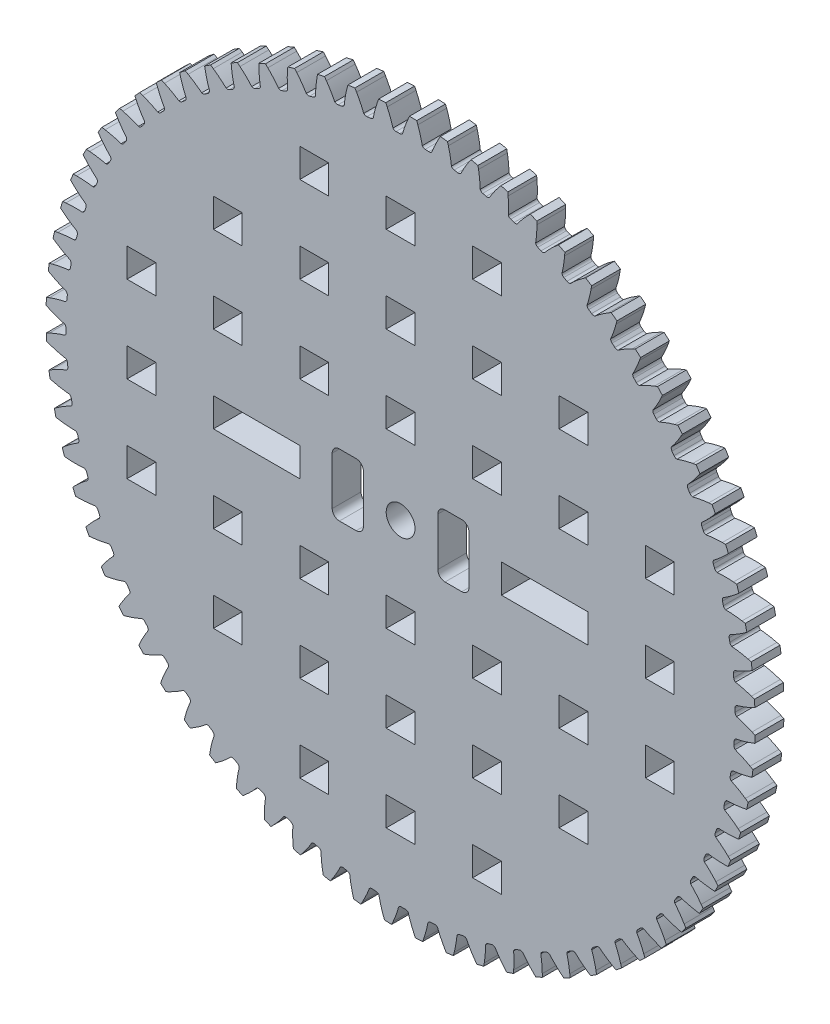
SolidWorks part; units mm, degrees
ref_plane "Alzado" through (0, 0, 0) normal (0, 0, 1) x (1, 0, 0)
ref_plane "Planta" through (0, 0, 0) normal (0, 1, 0) x (1, 0, 0)
ref_plane "Vista lateral" through (0, 0, 0) normal (1, 0, 0) x (0, 0, -1)
sketch "Model" plane through (0, 0, 0) normal (0, 0, 1) x (1, 0, 0)
  line L0 (42.6187, 265.9479) -> (42.6187, 262.9479)
  line L1 (45.6187, 265.9479) -> (42.6187, 265.9479)
  line L2 (45.6187, 262.9479) -> (45.6187, 265.9479)
  line L3 (42.6187, 262.9479) -> (45.6187, 262.9479)
  line L4 (72.6187, 238.9479) -> (69.6187, 238.9479)
  line L5 (72.6187, 235.9479) -> (72.6187, 238.9479)
  line L6 (69.6187, 235.9479) -> (72.6187, 235.9479)
  line L7 (69.6187, 238.9479) -> (69.6187, 235.9479)
  line L8 (72.6187, 256.9479) -> (69.6187, 256.9479)
  line L9 (72.6187, 253.9479) -> (72.6187, 256.9479)
  line L10 (69.6187, 253.9479) -> (72.6187, 253.9479)
  line L11 (69.6187, 256.9479) -> (69.6187, 253.9479)
  line L12 (42.6187, 256.9479) -> (42.6187, 253.9479)
  line L13 (45.6187, 256.9479) -> (42.6187, 256.9479)
  line L14 (45.6187, 253.9479) -> (45.6187, 256.9479)
  line L15 (42.6187, 253.9479) -> (45.6187, 253.9479)
  line L16 (51.6187, 256.9479) -> (51.6187, 253.9479)
  line L17 (54.6187, 256.9479) -> (51.6187, 256.9479)
  line L18 (54.6187, 253.9479) -> (54.6187, 256.9479)
  line L19 (51.6187, 253.9479) -> (54.6187, 253.9479)
  line L20 (60.6187, 256.9479) -> (60.6187, 253.9479)
  line L21 (63.6187, 256.9479) -> (60.6187, 256.9479)
  line L22 (63.6187, 253.9479) -> (63.6187, 256.9479)
  line L23 (60.6187, 253.9479) -> (63.6187, 253.9479)
  line L24 (42.6187, 238.9479) -> (42.6187, 235.9479)
  line L25 (45.6187, 238.9479) -> (42.6187, 238.9479)
  line L26 (45.6187, 235.9479) -> (45.6187, 238.9479)
  line L27 (42.6187, 235.9479) -> (45.6187, 235.9479)
  line L28 (51.6187, 238.9479) -> (51.6187, 235.9479)
  line L29 (54.6187, 238.9479) -> (51.6187, 238.9479)
  line L30 (54.6187, 235.9479) -> (54.6187, 238.9479)
  line L31 (51.6187, 235.9479) -> (54.6187, 235.9479)
  line L32 (60.6187, 238.9479) -> (60.6187, 235.9479)
  line L33 (63.6187, 238.9479) -> (60.6187, 238.9479)
  line L34 (63.6187, 235.9479) -> (63.6187, 238.9479)
  line L35 (60.6187, 235.9479) -> (63.6187, 235.9479)
  line L36 (42.6187, 229.9479) -> (42.6187, 226.9479)
  line L37 (45.6187, 229.9479) -> (42.6187, 229.9479)
  line L38 (45.6187, 226.9479) -> (45.6187, 229.9479)
  line L39 (42.6187, 226.9479) -> (45.6187, 226.9479)
  line L40 (51.6187, 229.9479) -> (51.6187, 226.9479)
  line L41 (54.6187, 229.9479) -> (51.6187, 229.9479)
  line L42 (54.6187, 226.9479) -> (54.6187, 229.9479)
  line L43 (51.6187, 226.9479) -> (54.6187, 226.9479)
  line L44 (60.6187, 229.9479) -> (60.6187, 226.9479)
  line L45 (63.6187, 229.9479) -> (60.6187, 229.9479)
  line L46 (63.6187, 226.9479) -> (63.6187, 229.9479)
  line L47 (60.6187, 226.9479) -> (63.6187, 226.9479)
  line L48 (36.6187, 238.9479) -> (33.6187, 238.9479)
  line L49 (36.6187, 235.9479) -> (36.6187, 238.9479)
  line L50 (33.6187, 235.9479) -> (36.6187, 235.9479)
  line L51 (33.6187, 238.9479) -> (33.6187, 235.9479)
  line L52 (36.6187, 256.9479) -> (33.6187, 256.9479)
  line L53 (36.6187, 253.9479) -> (36.6187, 256.9479)
  line L54 (33.6187, 253.9479) -> (36.6187, 253.9479)
  line L55 (33.6187, 256.9479) -> (33.6187, 253.9479)
  line L56 (33.6187, 247.9479) -> (33.6187, 244.9479)
  line L57 (42.6187, 247.9479) -> (33.6187, 247.9479)
  line L58 (42.6187, 244.9479) -> (42.6187, 247.9479)
  line L59 (33.6187, 244.9479) -> (42.6187, 244.9479)
  line L60 (60.6187, 274.9479) -> (60.6187, 271.9479)
  line L61 (63.6187, 274.9479) -> (60.6187, 274.9479)
  line L62 (63.6187, 271.9479) -> (63.6187, 274.9479)
  line L63 (60.6187, 271.9479) -> (63.6187, 271.9479)
  line L64 (51.6187, 274.9479) -> (51.6187, 271.9479)
  line L65 (54.6187, 274.9479) -> (51.6187, 274.9479)
  line L66 (54.6187, 271.9479) -> (54.6187, 274.9479)
  line L67 (51.6187, 271.9479) -> (54.6187, 271.9479)
  line L68 (42.6187, 274.9479) -> (42.6187, 271.9479)
  line L69 (45.6187, 274.9479) -> (42.6187, 274.9479)
  line L70 (45.6187, 271.9479) -> (45.6187, 274.9479)
  line L71 (42.6187, 271.9479) -> (45.6187, 271.9479)
  line L72 (24.6187, 253.9479) -> (27.6187, 253.9479)
  line L73 (24.6187, 256.9479) -> (24.6187, 253.9479)
  line L74 (27.6187, 256.9479) -> (24.6187, 256.9479)
  line L75 (27.6187, 253.9479) -> (27.6187, 256.9479)
  line L76 (24.6187, 244.9479) -> (27.6187, 244.9479)
  line L77 (24.6187, 247.9479) -> (24.6187, 244.9479)
  line L78 (27.6187, 247.9479) -> (24.6187, 247.9479)
  line L79 (27.6187, 244.9479) -> (27.6187, 247.9479)
  line L80 (24.6187, 235.9479) -> (27.6187, 235.9479)
  line L81 (24.6187, 238.9479) -> (24.6187, 235.9479)
  line L82 (27.6187, 238.9479) -> (24.6187, 238.9479)
  line L83 (27.6187, 235.9479) -> (27.6187, 238.9479)
  line L84 (45.6187, 217.9479) -> (45.6187, 220.9479)
  line L85 (42.6187, 217.9479) -> (45.6187, 217.9479)
  line L86 (42.6187, 220.9479) -> (42.6187, 217.9479)
  line L87 (45.6187, 220.9479) -> (42.6187, 220.9479)
  line L88 (54.6187, 217.9479) -> (54.6187, 220.9479)
  line L89 (51.6187, 217.9479) -> (54.6187, 217.9479)
  line L90 (51.6187, 220.9479) -> (51.6187, 217.9479)
  line L91 (54.6187, 220.9479) -> (51.6187, 220.9479)
  line L92 (63.6187, 217.9479) -> (63.6187, 220.9479)
  line L93 (60.6187, 217.9479) -> (63.6187, 217.9479)
  line L94 (60.6187, 220.9479) -> (60.6187, 217.9479)
  line L95 (63.6187, 220.9479) -> (60.6187, 220.9479)
  line L96 (81.6187, 238.9479) -> (78.6187, 238.9479)
  line L97 (81.6187, 235.9479) -> (81.6187, 238.9479)
  line L98 (78.6187, 235.9479) -> (81.6187, 235.9479)
  line L99 (78.6187, 238.9479) -> (78.6187, 235.9479)
  line L100 (81.6187, 247.9479) -> (78.6187, 247.9479)
  line L101 (81.6187, 244.9479) -> (81.6187, 247.9479)
  line L102 (78.6187, 244.9479) -> (81.6187, 244.9479)
  line L103 (78.6187, 247.9479) -> (78.6187, 244.9479)
  line L104 (81.6187, 256.9479) -> (78.6187, 256.9479)
  line L105 (81.6187, 253.9479) -> (81.6187, 256.9479)
  line L106 (78.6187, 253.9479) -> (81.6187, 253.9479)
  line L107 (78.6187, 256.9479) -> (78.6187, 253.9479)
  line L108 (33.6187, 265.9479) -> (33.6187, 262.9479)
  line L109 (36.6187, 265.9479) -> (33.6187, 265.9479)
  line L110 (36.6187, 262.9479) -> (36.6187, 265.9479)
  line L111 (33.6187, 262.9479) -> (36.6187, 262.9479)
  line L112 (33.6187, 229.9479) -> (33.6187, 226.9479)
  line L113 (36.6187, 229.9479) -> (33.6187, 229.9479)
  line L114 (36.6187, 226.9479) -> (36.6187, 229.9479)
  line L115 (33.6187, 226.9479) -> (36.6187, 226.9479)
  line L116 (69.6187, 265.9479) -> (69.6187, 262.9479)
  line L117 (72.6187, 265.9479) -> (69.6187, 265.9479)
  line L118 (72.6187, 262.9479) -> (72.6187, 265.9479)
  line L119 (69.6187, 262.9479) -> (72.6187, 262.9479)
  line L120 (69.6187, 229.9479) -> (69.6187, 226.9479)
  line L121 (72.6187, 229.9479) -> (69.6187, 229.9479)
  line L122 (72.6187, 226.9479) -> (72.6187, 229.9479)
  line L123 (69.6187, 226.9479) -> (72.6187, 226.9479)
  line L124 (51.6187, 265.9479) -> (51.6187, 262.9479)
  line L125 (54.6187, 265.9479) -> (51.6187, 265.9479)
  line L126 (54.6187, 262.9479) -> (54.6187, 265.9479)
  line L127 (51.6187, 262.9479) -> (54.6187, 262.9479)
  line L128 (63.6187, 247.9479) -> (63.6187, 244.9479)
  line L129 (72.6187, 247.9479) -> (63.6187, 247.9479)
  line L130 (72.6187, 244.9479) -> (72.6187, 247.9479)
  line L131 (63.6187, 244.9479) -> (72.6187, 244.9479)
  line L132 (60.6187, 265.9479) -> (60.6187, 262.9479)
  line L133 (63.6187, 265.9479) -> (60.6187, 265.9479)
  line L134 (63.6187, 262.9479) -> (63.6187, 265.9479)
  line L135 (60.6187, 262.9479) -> (63.6187, 262.9479)
  line L136 (59.4937, 249.6979) -> (57.7437, 249.6979)
  line L137 (60.2437, 243.9479) -> (60.2437, 248.9479)
  line L138 (57.7437, 243.1979) -> (59.4937, 243.1979)
  line L139 (56.9937, 248.9479) -> (56.9937, 243.9479)
  line L140 (46.7437, 249.6979) -> (48.4937, 249.6979)
  line L141 (45.9937, 243.9479) -> (45.9937, 248.9479)
  line L142 (48.4937, 243.1979) -> (46.7437, 243.1979)
  line L143 (49.2437, 248.9479) -> (49.2437, 243.9479)
  line L144 (66.3811, 280.5801) -> (66.6218, 280.8256)
  line L145 (66.6218, 280.8256) -> (67.3121, 280.5464)
  line L146 (67.3121, 280.5464) -> (67.3144, 280.2026)
  line L147 (67.4112, 278.2246) -> (67.7482, 278.0709)
  line L148 (69.3055, 279.2944) -> (69.5666, 279.5179)
  line L149 (69.5666, 279.5179) -> (70.23, 279.1796)
  line L150 (70.23, 279.1796) -> (70.2023, 278.837)
  line L151 (70.1264, 276.8581) -> (70.4487, 276.6755)
  line L152 (72.1066, 277.7586) -> (72.3862, 277.9586)
  line L153 (72.3862, 277.9586) -> (73.0176, 277.5637)
  line L154 (73.0176, 277.5637) -> (72.9602, 277.2248)
  line L155 (72.712, 275.26) -> (73.0172, 275.0501)
  line L156 (74.7633, 275.9846) -> (75.0593, 276.1594)
  line L157 (75.0593, 276.1594) -> (75.6538, 275.711)
  line L158 (75.6538, 275.711) -> (75.5671, 275.3784)
  line L159 (75.1486, 273.4427) -> (75.4344, 273.207)
  line L160 (77.2552, 273.9857) -> (77.5653, 274.1341)
  line L161 (77.5653, 274.1341) -> (78.1185, 273.6356)
  line L162 (78.1185, 273.6356) -> (78.0031, 273.3118)
  line L163 (77.4176, 271.42) -> (77.6817, 271.1602)
  line L164 (79.5634, 271.7773) -> (79.8853, 271.8981)
  line L165 (79.8853, 271.8981) -> (80.3929, 271.3533)
  line L166 (80.3929, 271.3533) -> (80.2498, 271.0407)
  line L167 (79.5015, 269.2072) -> (79.742, 268.9254)
  line L168 (81.6704, 269.3761) -> (82.0015, 269.4684)
  line L169 (82.0015, 269.4684) -> (82.4598, 268.8814)
  line L170 (82.4598, 268.8814) -> (82.2899, 268.5825)
  line L171 (81.3847, 266.8211) -> (81.5997, 266.5195)
  line L172 (83.5601, 266.8004) -> (83.898, 266.8635)
  line L173 (83.898, 266.8635) -> (84.3033, 266.2388)
  line L174 (84.3033, 266.2388) -> (84.1081, 265.9559)
  line L175 (83.0528, 264.2801) -> (83.2407, 263.9608)
  line L176 (85.2181, 264.0698) -> (85.5602, 264.1032)
  line L177 (85.5602, 264.1032) -> (85.9096, 263.4455)
  line L178 (85.9096, 263.4455) -> (85.6904, 263.1807)
  line L179 (84.4931, 261.6033) -> (84.6524, 261.2689)
  line L180 (86.6318, 261.2051) -> (86.9755, 261.2086)
  line L181 (86.9755, 261.2086) -> (87.2662, 260.523)
  line L182 (87.2662, 260.523) -> (87.0248, 260.2782)
  line L183 (85.6946, 258.8112) -> (85.8242, 258.4641)
  line L184 (87.7904, 258.2281) -> (88.1332, 258.2016)
  line L185 (88.1332, 258.2016) -> (88.363, 257.4932)
  line L186 (88.363, 257.4932) -> (88.1012, 257.2705)
  line L187 (86.6481, 255.9249) -> (86.747, 255.568)
  line L188 (88.6852, 255.1615) -> (89.0243, 255.1051)
  line L189 (89.0243, 255.1051) -> (89.1916, 254.3795)
  line L190 (89.1916, 254.3795) -> (88.9113, 254.1804)
  line L191 (87.3465, 252.9666) -> (87.4139, 252.6024)
  line L192 (89.3093, 252.0285) -> (89.6422, 251.9428)
  line L193 (89.6422, 251.9428) -> (89.7456, 251.2053)
  line L194 (89.7456, 251.2053) -> (89.449, 251.0315)
  line L195 (87.7844, 249.9586) -> (87.8198, 249.5899)
  line L196 (89.658, 248.853) -> (89.9821, 248.7387)
  line L197 (89.9821, 248.7387) -> (90.0208, 247.995)
  line L198 (90.0208, 247.995) -> (89.7103, 247.8476)
  line L199 (87.9585, 246.924) -> (87.9616, 246.5536)
  line L200 (89.7285, 245.6593) -> (90.0415, 245.5171)
  line L201 (90.0415, 245.5171) -> (90.0152, 244.7729)
  line L202 (90.0152, 244.7729) -> (89.693, 244.6531)
  line L203 (87.8674, 243.8857) -> (87.8382, 243.5164)
  line L204 (89.5205, 242.4715) -> (89.8199, 242.3026)
  line L205 (89.8199, 242.3026) -> (89.7288, 241.5635)
  line L206 (89.7288, 241.5635) -> (89.3974, 241.4723)
  line L207 (87.5119, 240.8669) -> (87.4506, 240.5016)
  line L208 (89.0354, 239.314) -> (89.3189, 239.1197)
  line L209 (89.3189, 239.1197) -> (89.1638, 238.3913)
  line L210 (89.1638, 238.3913) -> (88.8257, 238.3293)
  line L211 (86.8946, 237.8906) -> (86.8017, 237.532)
  line L212 (88.277, 236.2108) -> (88.5425, 235.9925)
  line L213 (88.5425, 235.9925) -> (88.3245, 235.2804)
  line L214 (88.3245, 235.2804) -> (87.9823, 235.2482)
  line L215 (86.0202, 234.9794) -> (85.8964, 234.6302)
  line L216 (87.251, 233.1856) -> (87.4964, 232.9449)
  line L217 (87.4964, 232.9449) -> (87.2172, 232.2546)
  line L218 (87.2172, 232.2546) -> (86.8735, 232.2522)
  line L219 (84.8955, 232.1555) -> (84.7417, 231.8184)
  line L220 (85.9652, 230.2612) -> (86.1888, 230.0001)
  line L221 (86.1888, 230.0001) -> (85.8504, 229.3367)
  line L222 (85.8504, 229.3367) -> (85.5078, 229.3643)
  line L223 (83.5289, 229.4403) -> (83.3463, 229.118)
  line L224 (84.4294, 227.46) -> (84.6294, 227.1804)
  line L225 (84.6294, 227.1804) -> (84.2345, 226.549)
  line L226 (84.2345, 226.549) -> (83.8956, 226.6064)
  line L227 (81.9308, 226.8546) -> (81.7209, 226.5494)
  line L228 (82.6554, 224.8034) -> (82.8302, 224.5074)
  line L229 (82.8302, 224.5074) -> (82.3818, 223.9128)
  line L230 (82.3818, 223.9128) -> (82.0492, 223.9996)
  line L231 (80.1135, 224.418) -> (79.8778, 224.1323)
  line L232 (80.6565, 222.3115) -> (80.8049, 222.0014)
  line L233 (80.8049, 222.0014) -> (80.3064, 221.4482)
  line L234 (80.3064, 221.4482) -> (79.9826, 221.5635)
  line L235 (78.0908, 222.1491) -> (77.831, 221.885)
  line L236 (78.4481, 220.0032) -> (78.5689, 219.6814)
  line L237 (78.5689, 219.6814) -> (78.0241, 219.1737)
  line L238 (78.0241, 219.1737) -> (77.7115, 219.3169)
  line L239 (75.878, 220.0651) -> (75.5962, 219.8247)
  line L240 (76.0469, 217.8963) -> (76.1392, 217.5651)
  line L241 (76.1392, 217.5651) -> (75.5522, 217.1069)
  line L242 (75.5522, 217.1069) -> (75.2533, 217.2767)
  line L243 (73.492, 218.1819) -> (73.1903, 217.9669)
  line L244 (73.4712, 216.0066) -> (73.5343, 215.6687)
  line L245 (73.5343, 215.6687) -> (72.9096, 215.2633)
  line L246 (72.9096, 215.2633) -> (72.6267, 215.4586)
  line L247 (70.9509, 216.5138) -> (70.6316, 216.326)
  line L248 (70.7407, 214.3486) -> (70.774, 214.0065)
  line L249 (70.774, 214.0065) -> (70.1164, 213.6571)
  line L250 (70.1164, 213.6571) -> (69.8515, 213.8763)
  line L251 (68.2741, 215.0736) -> (67.9397, 214.9142)
  line L252 (67.876, 212.9349) -> (67.8794, 212.5912)
  line L253 (67.8794, 212.5912) -> (67.1938, 212.3004)
  line L254 (67.1938, 212.3004) -> (66.9491, 212.5419)
  line L255 (65.482, 213.8721) -> (65.135, 213.7425)
  line L256 (64.899, 211.7762) -> (64.8724, 211.4335)
  line L257 (64.8724, 211.4335) -> (64.1641, 211.2037)
  line L258 (64.1641, 211.2037) -> (63.9413, 211.4655)
  line L259 (62.5958, 212.9185) -> (62.2388, 212.8197)
  line L260 (61.8323, 210.8815) -> (61.776, 210.5424)
  line L261 (61.776, 210.5424) -> (61.0503, 210.3751)
  line L262 (61.0503, 210.3751) -> (60.8512, 210.6554)
  line L263 (59.6374, 212.2201) -> (59.2732, 212.1528)
  line L264 (58.6993, 210.2574) -> (58.6136, 209.9245)
  line L265 (58.6136, 209.9245) -> (57.8762, 209.8211)
  line L266 (57.8762, 209.8211) -> (57.7023, 210.1176)
  line L267 (56.6295, 211.7822) -> (56.2607, 211.7469)
  line L268 (55.5239, 209.9087) -> (55.4095, 209.5845)
  line L269 (55.4095, 209.5845) -> (54.6658, 209.5458)
  line L270 (54.6658, 209.5458) -> (54.5184, 209.8564)
  line L271 (53.5948, 211.6082) -> (53.2244, 211.6051)
  line L272 (52.3301, 209.8381) -> (52.1879, 209.5252)
  line L273 (52.1879, 209.5252) -> (51.4437, 209.5514)
  line L274 (51.4437, 209.5514) -> (51.3239, 209.8736)
  line L275 (50.5565, 211.6993) -> (50.1872, 211.7285)
  line L276 (49.1424, 210.0462) -> (48.9734, 209.7468)
  line L277 (48.9734, 209.7468) -> (48.2343, 209.8378)
  line L278 (48.2343, 209.8378) -> (48.1431, 210.1693)
  line L279 (47.5377, 212.0548) -> (47.1724, 212.1161)
  line L280 (45.9849, 210.5313) -> (45.7905, 210.2477)
  line L281 (45.7905, 210.2477) -> (45.0621, 210.4028)
  line L282 (45.0621, 210.4028) -> (45.0002, 210.741)
  line L283 (44.5614, 212.6721) -> (44.2028, 212.765)
  line L284 (42.8817, 211.2897) -> (42.6633, 211.0242)
  line L285 (42.6633, 211.0242) -> (41.9513, 211.2422)
  line L286 (41.9513, 211.2422) -> (41.919, 211.5844)
  line L287 (41.6502, 213.5465) -> (41.3011, 213.6702)
  line L288 (39.8564, 212.3157) -> (39.6157, 212.0702)
  line L289 (39.6157, 212.0702) -> (38.9254, 212.3495)
  line L290 (38.9254, 212.3495) -> (38.923, 212.6932)
  line L291 (38.8263, 214.6712) -> (38.4893, 214.8249)
  line L292 (36.932, 213.6015) -> (36.6709, 213.3779)
  line L293 (36.6709, 213.3779) -> (36.0075, 213.7162)
  line L294 (36.0075, 213.7162) -> (36.0351, 214.0589)
  line L295 (36.1111, 216.0378) -> (35.7888, 216.2203)
  line L296 (34.1309, 215.1372) -> (33.8513, 214.9373)
  line L297 (33.8513, 214.9373) -> (33.2199, 215.3321)
  line L298 (33.2199, 215.3321) -> (33.2773, 215.6711)
  line L299 (33.5254, 217.6358) -> (33.2202, 217.8457)
  line L300 (31.4742, 216.9113) -> (31.1782, 216.7365)
  line L301 (31.1782, 216.7365) -> (30.5837, 217.1848)
  line L302 (30.5837, 217.1848) -> (30.6704, 217.5175)
  line L303 (31.0889, 219.4531) -> (30.8031, 219.6889)
  line L304 (28.9823, 218.9101) -> (28.6722, 218.7618)
  line L305 (28.6722, 218.7618) -> (28.119, 219.2603)
  line L306 (28.119, 219.2603) -> (28.2344, 219.5841)
  line L307 (28.8199, 221.4759) -> (28.5558, 221.7356)
  line L308 (26.6741, 221.1185) -> (26.3522, 220.9978)
  line L309 (26.3522, 220.9978) -> (25.8445, 221.5426)
  line L310 (25.8445, 221.5426) -> (25.9877, 221.8551)
  line L311 (26.7359, 223.6887) -> (26.4955, 223.9705)
  line L312 (24.5671, 223.5197) -> (24.2359, 223.4275)
  line L313 (24.2359, 223.4275) -> (23.7777, 224.0145)
  line L314 (23.7777, 224.0145) -> (23.9476, 224.3133)
  line L315 (24.8527, 226.0747) -> (24.6378, 226.3764)
  line L316 (22.6774, 226.0954) -> (22.3395, 226.0324)
  line L317 (22.3395, 226.0324) -> (21.9341, 226.6571)
  line L318 (21.9341, 226.6571) -> (22.1294, 226.94)
  line L319 (23.1847, 228.6158) -> (22.9968, 228.935)
  line L320 (21.0194, 228.826) -> (20.6773, 228.7926)
  line L321 (20.6773, 228.7926) -> (20.3279, 229.4503)
  line L322 (20.3279, 229.4503) -> (20.5471, 229.7151)
  line L323 (21.7444, 231.2926) -> (21.5851, 231.627)
  line L324 (19.6057, 231.6907) -> (19.262, 231.6873)
  line L325 (19.262, 231.6873) -> (18.9713, 232.3729)
  line L326 (18.9713, 232.3729) -> (19.2127, 232.6176)
  line L327 (20.5429, 234.0847) -> (20.4133, 234.4317)
  line L328 (18.4471, 234.6677) -> (18.1043, 234.6943)
  line L329 (18.1043, 234.6943) -> (17.8745, 235.4026)
  line L330 (17.8745, 235.4026) -> (18.1363, 235.6253)
  line L331 (19.5893, 236.9709) -> (19.4905, 237.3279)
  line L332 (17.5523, 237.7344) -> (17.2132, 237.7907)
  line L333 (17.2132, 237.7907) -> (17.0459, 238.5164)
  line L334 (17.0459, 238.5164) -> (17.3262, 238.7154)
  line L335 (18.891, 239.9293) -> (18.8236, 240.2935)
  line L336 (16.9282, 240.8674) -> (16.5953, 240.953)
  line L337 (16.5953, 240.953) -> (16.4919, 241.6905)
  line L338 (16.4919, 241.6905) -> (16.7885, 241.8644)
  line L339 (18.4531, 242.9372) -> (18.4177, 243.3059)
  line L340 (16.5795, 244.0428) -> (16.2554, 244.1572)
  line L341 (16.2554, 244.1572) -> (16.2167, 244.9008)
  line L342 (16.2167, 244.9008) -> (16.5272, 245.0482)
  line L343 (18.279, 245.9719) -> (18.2759, 246.3423)
  line L344 (16.509, 247.2366) -> (16.196, 247.3787)
  line L345 (16.196, 247.3787) -> (16.2222, 248.123)
  line L346 (16.2222, 248.123) -> (16.5445, 248.2427)
  line L347 (18.3701, 249.0102) -> (18.3993, 249.3794)
  line L348 (16.717, 250.4243) -> (16.4176, 250.5932)
  line L349 (16.4176, 250.5932) -> (16.5086, 251.3323)
  line L350 (16.5086, 251.3323) -> (16.8401, 251.4235)
  line L351 (18.7256, 252.029) -> (18.7869, 252.3943)
  line L352 (17.2021, 253.5818) -> (16.9186, 253.7762)
  line L353 (16.9186, 253.7762) -> (17.0737, 254.5045)
  line L354 (17.0737, 254.5045) -> (17.4118, 254.5665)
  line L355 (19.3429, 255.0053) -> (19.4358, 255.3639)
  line L356 (17.9605, 256.685) -> (17.695, 256.9033)
  line L357 (17.695, 256.9033) -> (17.913, 257.6154)
  line L358 (17.913, 257.6154) -> (18.2552, 257.6477)
  line L359 (20.2173, 257.9165) -> (20.3411, 258.2656)
  line L360 (18.9865, 259.7103) -> (18.741, 259.9509)
  line L361 (18.741, 259.9509) -> (19.0203, 260.6413)
  line L362 (19.0203, 260.6413) -> (19.364, 260.6436)
  line L363 (21.342, 260.7404) -> (21.4958, 261.0774)
  line L364 (20.2723, 262.6346) -> (20.0487, 262.8958)
  line L365 (20.0487, 262.8958) -> (20.3871, 263.5592)
  line L366 (20.3871, 263.5592) -> (20.7297, 263.5315)
  line L367 (22.7086, 263.4555) -> (22.8911, 263.7779)
  line L368 (21.8081, 265.4358) -> (21.6081, 265.7154)
  line L369 (21.6081, 265.7154) -> (22.003, 266.3468)
  line L370 (22.003, 266.3468) -> (22.3419, 266.2894)
  line L371 (24.3066, 266.0412) -> (24.5166, 266.3464)
  line L372 (23.5821, 268.0925) -> (23.4073, 268.3884)
  line L373 (23.4073, 268.3884) -> (23.8557, 268.983)
  line L374 (23.8557, 268.983) -> (24.1883, 268.8963)
  line L375 (26.124, 268.4778) -> (26.3597, 268.7635)
  line L376 (25.5809, 270.5844) -> (25.4326, 270.8945)
  line L377 (25.4326, 270.8945) -> (25.9311, 271.4477)
  line L378 (25.9311, 271.4477) -> (26.2549, 271.3323)
  line L379 (28.1467, 270.7467) -> (28.4064, 271.0108)
  line L380 (27.7894, 272.8926) -> (27.6686, 273.2144)
  line L381 (27.6686, 273.2144) -> (28.2134, 273.7221)
  line L382 (28.2134, 273.7221) -> (28.5259, 273.579)
  line L383 (30.3595, 272.8307) -> (30.6413, 273.0712)
  line L384 (30.1906, 274.9996) -> (30.0983, 275.3307)
  line L385 (30.0983, 275.3307) -> (30.6853, 275.789)
  line L386 (30.6853, 275.789) -> (30.9841, 275.6191)
  line L387 (32.7455, 274.7139) -> (33.0472, 274.9289)
  line L388 (32.7662, 276.8893) -> (32.7032, 277.2272)
  line L389 (32.7032, 277.2272) -> (33.3279, 277.6325)
  line L390 (33.3279, 277.6325) -> (33.6108, 277.4373)
  line L391 (35.2866, 276.382) -> (35.6058, 276.5699)
  line L392 (35.4968, 278.5473) -> (35.4635, 278.8894)
  line L393 (35.4635, 278.8894) -> (36.1211, 279.2387)
  line L394 (36.1211, 279.2387) -> (36.3859, 279.0196)
  line L395 (37.9634, 277.8223) -> (38.2978, 277.9816)
  line L396 (38.3615, 279.961) -> (38.3581, 280.3047)
  line L397 (38.3581, 280.3047) -> (39.0437, 280.5954)
  line L398 (39.0437, 280.5954) -> (39.2884, 280.354)
  line L399 (40.7555, 279.0238) -> (41.1025, 279.1534)
  line L400 (41.3385, 281.1196) -> (41.3651, 281.4623)
  line L401 (41.3651, 281.4623) -> (42.0734, 281.6922)
  line L402 (42.0734, 281.6922) -> (42.2962, 281.4304)
  line L403 (43.6417, 279.9773) -> (43.9987, 280.0762)
  line L404 (44.4052, 282.0144) -> (44.4615, 282.3535)
  line L405 (44.4615, 282.3535) -> (45.1872, 282.5207)
  line L406 (45.1872, 282.5207) -> (45.3863, 282.2405)
  line L407 (46.6001, 280.6757) -> (46.9643, 280.7431)
  line L408 (47.5382, 282.6385) -> (47.6238, 282.9714)
  line L409 (47.6238, 282.9714) -> (48.3613, 283.0747)
  line L410 (48.3613, 283.0747) -> (48.5352, 282.7782)
  line L411 (49.608, 281.1136) -> (49.9768, 281.149)
  line L412 (50.7136, 282.9871) -> (50.828, 283.3113)
  line L413 (50.828, 283.3113) -> (51.5717, 283.35)
  line L414 (51.5717, 283.35) -> (51.7191, 283.0394)
  line L415 (52.6427, 281.2877) -> (53.0131, 281.2908)
  line L416 (53.9074, 283.0577) -> (54.0496, 283.3707)
  line L417 (54.0496, 283.3707) -> (54.7938, 283.3444)
  line L418 (54.7938, 283.3444) -> (54.9135, 283.0222)
  line L419 (55.681, 281.1966) -> (56.0503, 281.1674)
  line L420 (57.0951, 282.8497) -> (57.264, 283.1491)
  line L421 (57.264, 283.1491) -> (58.0032, 283.058)
  line L422 (58.0032, 283.058) -> (58.0944, 282.7266)
  line L423 (58.6998, 280.841) -> (59.0651, 280.7798)
  line L424 (60.2526, 282.3646) -> (60.447, 282.6481)
  line L425 (60.447, 282.6481) -> (61.1753, 282.493)
  line L426 (61.1753, 282.493) -> (61.2373, 282.1549)
  line L427 (61.6761, 280.2237) -> (62.0347, 280.1309)
  line L428 (63.3558, 281.6062) -> (63.5742, 281.8717)
  line L429 (63.5742, 281.8717) -> (64.2862, 281.6537)
  line L430 (64.2862, 281.6537) -> (64.3185, 281.3114)
  line L431 (64.5873, 279.3494) -> (64.9364, 279.2256)
  circle A0 centre (53.1187, 246.4479) radius 1.5
  arc A1 (57.7437, 249.6979) -> (56.9937, 248.9479) centre (57.7437, 248.9479) ccw
  arc A2 (60.2437, 248.9479) -> (59.4937, 249.6979) centre (59.4937, 248.9479) ccw
  arc A3 (59.4937, 243.1979) -> (60.2437, 243.9479) centre (59.4937, 243.9479) ccw
  arc A4 (56.9937, 243.9479) -> (57.7437, 243.1979) centre (57.7437, 243.9479) ccw
  arc A5 (49.2437, 248.9479) -> (48.4937, 249.6979) centre (48.4937, 248.9479) ccw
  arc A6 (46.7437, 249.6979) -> (45.9937, 248.9479) centre (46.7437, 248.9479) ccw
  arc A7 (45.9937, 243.9479) -> (46.7437, 243.1979) centre (46.7437, 243.9479) ccw
  arc A8 (48.4937, 243.1979) -> (49.2437, 243.9479) centre (48.4937, 243.9479) ccw
  arc A9 (64.9364, 279.2256) -> (65.2859, 279.265) centre (65.0725, 279.5883) ccw
  arc A10 (66.3811, 280.5801) -> (65.2859, 279.265) centre (74.0922, 273.0451) ccw
  arc A11 (67.1874, 278.4959) -> (67.3144, 280.2026) centre (56.5333, 280.1472) ccw
  arc A12 (67.1874, 278.4959) -> (67.4112, 278.2246) centre (67.5655, 278.5799) ccw
  arc A13 (67.7482, 278.0709) -> (68.0998, 278.0797) centre (67.9154, 278.4203) ccw
  arc A14 (69.3055, 279.2944) -> (68.0998, 278.0797) centre (76.3305, 271.116) ccw
  arc A15 (69.927, 277.1478) -> (70.2023, 278.837) centre (59.4573, 279.7213) ccw
  arc A16 (69.927, 277.1478) -> (70.1264, 276.8581) centre (70.311, 277.1985) ccw
  arc A17 (70.4487, 276.6755) -> (70.7997, 276.6536) centre (70.6457, 277.009) ccw
  arc A18 (72.1066, 277.7586) -> (70.7997, 276.6536) centre (78.3921, 268.9991) ccw
  arc A19 (72.5387, 275.566) -> (72.9602, 277.2248) centre (62.3332, 279.0423) ccw
  arc A20 (72.5387, 275.566) -> (72.712, 275.26) centre (72.9257, 275.5831) ccw
  arc A21 (73.0172, 275.0501) -> (73.365, 274.9977) centre (73.2426, 275.3652) ccw
  arc A22 (74.7633, 275.9846) -> (73.365, 274.9977) centre (80.2614, 266.7105) ccw
  arc A23 (75.0026, 273.7627) -> (75.5671, 275.3784) centre (65.1389, 278.1152) ccw
  arc A24 (75.0026, 273.7627) -> (75.1486, 273.4427) centre (75.3896, 273.746) ccw
  arc A25 (75.4344, 273.207) -> (75.7762, 273.1245) centre (75.6863, 273.5012) ccw
  arc A26 (77.2552, 273.9857) -> (75.7762, 273.1245) centre (81.9241, 264.2678) ccw
  arc A27 (77.3, 271.7514) -> (78.0031, 273.3118) centre (67.8532, 276.947) ccw
  arc A28 (77.3, 271.7514) -> (77.4176, 271.42) centre (77.684, 271.7011) ccw
  arc A29 (77.6817, 271.1602) -> (78.015, 271.0482) centre (77.9583, 271.4314) ccw
  arc A30 (79.5634, 271.7773) -> (78.015, 271.0482) centre (83.3676, 261.6894) ccw
  arc A31 (79.4133, 269.5476) -> (80.2498, 271.0407) centre (70.4553, 275.5468) ccw
  arc A32 (79.4133, 269.5476) -> (79.5015, 269.2072) centre (79.7915, 269.4639) ccw
  arc A33 (79.742, 268.9254) -> (80.0644, 268.7848) centre (80.0412, 269.1714) ccw
  arc A34 (81.6704, 269.3761) -> (80.0644, 268.7848) centre (84.5809, 258.9951) ccw
  arc A35 (81.3265, 267.168) -> (82.2899, 268.5825) centre (72.9254, 273.9251) ccw
  arc A36 (81.3265, 267.168) -> (81.3847, 266.8211) centre (81.696, 267.0517) ccw
  arc A37 (81.5997, 266.5195) -> (81.9086, 266.3513) centre (81.9192, 266.7385) ccw
  arc A38 (83.5601, 266.8004) -> (81.9086, 266.3513) centre (85.5547, 256.2052) ccw
  arc A39 (83.0251, 264.6307) -> (84.1081, 265.9559) centre (75.2448, 272.0942) ccw
  arc A40 (83.0251, 264.6307) -> (83.0528, 264.2801) centre (83.383, 264.4826) ccw
  arc A41 (83.2407, 263.9608) -> (83.5337, 263.7664) centre (83.5781, 264.1511) ccw
  arc A42 (85.2181, 264.0698) -> (83.5337, 263.7664) centre (86.2817, 253.3411) ccw
  arc A43 (84.496, 261.955) -> (85.6904, 263.1807) centre (77.3959, 270.0682) ccw
  arc A44 (84.496, 261.955) -> (84.4931, 261.6033) centre (84.8396, 261.7763) ccw
  arc A45 (84.6524, 261.2689) -> (84.9274, 261.0496) centre (85.0051, 261.4291) ccw
  arc A46 (86.6318, 261.2051) -> (84.9274, 261.0496) centre (86.7563, 250.4245) ccw
  arc A47 (85.7281, 259.1612) -> (87.0248, 260.2782) centre (79.3621, 267.8625) ccw
  arc A48 (85.7281, 259.1612) -> (85.6946, 258.8112) centre (86.0549, 258.9533) ccw
  arc A49 (85.8242, 258.4641) -> (86.079, 258.2217) centre (86.1895, 258.593) ccw
  arc A50 (87.7904, 258.2281) -> (86.079, 258.2217) centre (86.9749, 247.4777) ccw
  arc A51 (86.7121, 256.2708) -> (88.1012, 257.2705) centre (81.1287, 265.4937) ccw
  arc A52 (86.7121, 256.2708) -> (86.6481, 255.9249) centre (87.0195, 256.0351) ccw
  arc A53 (86.747, 255.568) -> (86.9797, 255.3043) centre (87.1221, 255.6645) ccw
  arc A54 (88.6852, 255.1615) -> (86.9797, 255.3043) centre (86.9358, 244.523) ccw
  arc A55 (87.4404, 253.3055) -> (88.9113, 254.1804) centre (82.682, 262.98) ccw
  arc A56 (87.4404, 253.3055) -> (87.3465, 252.9666) centre (87.7261, 253.044) ccw
  arc A57 (87.4139, 252.6024) -> (87.6227, 252.3194) centre (87.796, 252.6658) ccw
  arc A58 (89.3093, 252.0285) -> (87.6227, 252.3194) centre (86.6393, 241.583) ccw
  arc A59 (87.9074, 250.2881) -> (89.449, 251.0315) centre (84.0104, 260.3405) ccw
  arc A60 (87.9074, 250.2881) -> (87.7844, 249.9586) centre (88.1693, 250.0027) ccw
  arc A61 (87.8198, 249.5899) -> (88.0032, 249.2898) centre (88.206, 249.6198) ccw
  arc A62 (89.658, 248.853) -> (88.0032, 249.2898) centre (86.0878, 238.68) ccw
  arc A63 (88.1097, 247.2415) -> (89.7103, 247.8476) centre (85.1037, 257.5952) ccw
  arc A64 (88.1097, 247.2415) -> (87.9585, 246.924) centre (88.3457, 246.9343) ccw
  arc A65 (87.9616, 246.5536) -> (88.1181, 246.2386) centre (88.3489, 246.5497) ccw
  arc A66 (89.7285, 245.6593) -> (88.1181, 246.2386) centre (85.2853, 235.8361) ccw
  arc A67 (88.0458, 244.1888) -> (89.693, 244.6531) centre (85.9535, 254.7652) ccw
  arc A68 (88.0458, 244.1888) -> (87.8674, 243.8857) centre (88.254, 243.8622) ccw
  arc A69 (87.8382, 243.5164) -> (87.9667, 243.189) centre (88.2237, 243.4788) ccw
  arc A70 (89.5205, 242.4715) -> (87.9667, 243.189) centre (84.238, 233.073) ccw
  arc A71 (87.716, 241.1533) -> (89.3974, 241.4723) centre (86.5535, 251.8718) ccw
  arc A72 (87.716, 241.1533) -> (87.5119, 240.8669) centre (87.895, 240.8098) ccw
  arc A73 (87.4506, 240.5016) -> (87.5501, 240.1642) centre (87.8313, 240.4305) ccw
  arc A74 (89.0354, 239.314) -> (87.5501, 240.1642) centre (82.9539, 230.4117) ccw
  arc A75 (87.1228, 238.1581) -> (88.8257, 238.3293) centre (86.8989, 248.9371) ccw
  arc A76 (87.1228, 238.1581) -> (86.8946, 237.8906) centre (87.2712, 237.8003) ccw
  arc A77 (86.8017, 237.532) -> (86.8714, 237.1873) centre (87.1748, 237.428) ccw
  arc A78 (88.277, 236.2108) -> (86.8714, 237.1873) centre (81.4427, 227.8724) ccw
  arc A79 (86.2709, 235.226) -> (87.9823, 235.2482) centre (86.9873, 245.9835) ccw
  arc A80 (86.2709, 235.226) -> (86.0202, 234.9794) centre (86.3876, 234.8566) ccw
  arc A81 (85.8964, 234.6302) -> (85.9358, 234.2808) centre (86.2591, 234.4941) ccw
  arc A82 (87.251, 233.1856) -> (85.9358, 234.2808) centre (79.716, 225.4745) ccw
  arc A83 (85.1667, 232.3793) -> (86.8735, 232.2522) centre (86.818, 243.0334) ccw
  arc A84 (85.1667, 232.3793) -> (84.8955, 232.1555) centre (85.2507, 232.0012) ccw
  arc A85 (84.7417, 231.8184) -> (84.7505, 231.4669) centre (85.0911, 231.6513) ccw
  arc A86 (85.9652, 230.2612) -> (84.7505, 231.4669) centre (77.7868, 223.2362) ccw
  arc A87 (83.8186, 229.6397) -> (85.5078, 229.3643) centre (86.3922, 240.1093) ccw
  arc A88 (83.8186, 229.6397) -> (83.5289, 229.4403) centre (83.8694, 229.2557) ccw
  arc A89 (83.3463, 229.118) -> (83.3244, 228.767) centre (83.6798, 228.921) ccw
  arc A90 (84.4294, 227.46) -> (83.3244, 228.767) centre (75.6699, 221.1745) ccw
  arc A91 (82.2369, 227.0279) -> (83.8956, 226.6064) centre (85.7131, 237.2335) ccw
  arc A92 (82.2369, 227.0279) -> (81.9308, 226.8546) centre (82.2539, 226.641) ccw
  arc A93 (81.7209, 226.5494) -> (81.6685, 226.2017) centre (82.036, 226.3241) ccw
  arc A94 (82.6554, 224.8034) -> (81.6685, 226.2017) centre (73.3814, 219.3053) ccw
  arc A95 (80.4335, 224.564) -> (82.0492, 223.9996) centre (84.786, 234.4278) ccw
  arc A96 (80.4335, 224.564) -> (80.1135, 224.418) centre (80.4168, 224.1771) ccw
  arc A97 (79.8778, 224.1323) -> (79.7953, 223.7904) centre (80.172, 223.8804) ccw
  arc A98 (80.6565, 222.3115) -> (79.7953, 223.7904) centre (70.9386, 217.6425) ccw
  arc A99 (78.4222, 222.2667) -> (79.9826, 221.5635) centre (83.6178, 231.7135) ccw
  arc A100 (78.4222, 222.2667) -> (78.0908, 222.1491) centre (78.3719, 221.8826) ccw
  arc A101 (77.831, 221.885) -> (77.719, 221.5516) centre (78.1022, 221.6084) ccw
  arc A102 (78.4481, 220.0032) -> (77.719, 221.5516) centre (68.3603, 216.1991) ccw
  arc A103 (76.2184, 220.1533) -> (77.7115, 219.3169) centre (82.2176, 229.1114) ccw
  arc A104 (76.2184, 220.1533) -> (75.878, 220.0651) centre (76.1348, 219.7751) ccw
  arc A105 (75.5962, 219.8247) -> (75.4556, 219.5023) centre (75.8422, 219.5255) ccw
  arc A106 (76.0469, 217.8963) -> (75.4556, 219.5023) centre (65.6659, 214.9858) ccw
  arc A107 (73.8388, 218.2401) -> (75.2533, 217.2767) centre (80.5959, 226.6413) ccw
  arc A108 (73.8388, 218.2401) -> (73.492, 218.1819) centre (73.7225, 217.8707) ccw
  arc A109 (73.1903, 217.9669) -> (73.0221, 217.6581) centre (73.4093, 217.6474) ccw
  arc A110 (73.4712, 216.0066) -> (73.0221, 217.6581) centre (62.876, 214.0119) ccw
  arc A111 (71.3015, 216.5416) -> (72.6267, 215.4586) centre (78.7651, 224.3218) ccw
  arc A112 (71.3015, 216.5416) -> (70.9509, 216.5138) centre (71.1534, 216.1837) ccw
  arc A113 (70.6316, 216.326) -> (70.4372, 216.0329) centre (70.822, 215.9886) ccw
  arc A114 (70.7407, 214.3486) -> (70.4372, 216.0329) centre (60.0119, 213.285) ccw
  arc A115 (68.6258, 215.0707) -> (69.8515, 213.8763) centre (76.7391, 222.1708) ccw
  arc A116 (68.6258, 215.0707) -> (68.2741, 215.0736) centre (68.4471, 214.727) ccw
  arc A117 (67.9397, 214.9142) -> (67.7204, 214.6393) centre (68.0999, 214.5616) ccw
  arc A118 (67.876, 212.9349) -> (67.7204, 214.6393) centre (57.0954, 212.8104) ccw
  arc A119 (65.8321, 213.8385) -> (66.9491, 212.5419) centre (74.5333, 220.2045) ccw
  arc A120 (65.8321, 213.8385) -> (65.482, 213.8721) centre (65.6241, 213.5118) ccw
  arc A121 (65.135, 213.7425) -> (64.8926, 213.4877) centre (65.2638, 213.3772) ccw
  arc A122 (64.899, 211.7762) -> (64.8926, 213.4877) centre (54.1485, 212.5918) ccw
  arc A123 (62.9416, 212.8546) -> (63.9413, 211.4655) centre (72.1645, 218.438) ccw
  arc A124 (62.9416, 212.8546) -> (62.5958, 212.9185) centre (62.7059, 212.5472) ccw
  arc A125 (62.2388, 212.8197) -> (61.9751, 212.587) centre (62.3353, 212.4445) ccw
  arc A126 (61.8323, 210.8815) -> (61.9751, 212.587) centre (51.1938, 212.6309) ccw
  arc A127 (59.9764, 212.1263) -> (60.8512, 210.6554) centre (69.6508, 216.8846) ccw
  arc A128 (59.9764, 212.1263) -> (59.6374, 212.2201) centre (59.7148, 211.8406) ccw
  arc A129 (59.2732, 212.1528) -> (58.9902, 211.9439) centre (59.3366, 211.7707) ccw
  arc A130 (58.6993, 210.2574) -> (58.9902, 211.9439) centre (48.2538, 212.9273) ccw
  arc A131 (56.9589, 211.6592) -> (57.7023, 210.1176) centre (67.0113, 215.5563) ccw
  arc A132 (56.9589, 211.6592) -> (56.6295, 211.7822) centre (56.6735, 211.3974) ccw
  arc A133 (56.2607, 211.7469) -> (55.9606, 211.5635) centre (56.2906, 211.3607) ccw
  arc A134 (55.5239, 209.9087) -> (55.9606, 211.5635) centre (45.3508, 213.4789) ccw
  arc A135 (53.9123, 211.4569) -> (54.5184, 209.8564) centre (64.2661, 214.463) ccw
  arc A136 (53.9123, 211.4569) -> (53.5948, 211.6082) centre (53.6051, 211.221) ccw
  arc A137 (53.2244, 211.6051) -> (52.9094, 211.4485) centre (53.2205, 211.2178) ccw
  arc A138 (52.3301, 209.8381) -> (52.9094, 211.4485) centre (42.5069, 214.2814) ccw
  arc A139 (50.8596, 211.5209) -> (51.3239, 209.8736) centre (61.436, 213.6132) ccw
  arc A140 (50.8596, 211.5209) -> (50.5565, 211.6993) centre (50.533, 211.3126) ccw
  arc A141 (50.1872, 211.7285) -> (49.8598, 211.6) centre (50.1496, 211.343) ccw
  arc A142 (49.1424, 210.0462) -> (49.8598, 211.6) centre (39.7438, 215.3287) ccw
  arc A143 (47.8241, 211.8507) -> (48.1431, 210.1693) centre (58.5426, 213.0132) ccw
  arc A144 (47.8241, 211.8507) -> (47.5377, 212.0548) centre (47.4806, 211.6717) ccw
  arc A145 (47.1724, 212.1161) -> (46.835, 212.0166) centre (47.1013, 211.7353) ccw
  arc A146 (45.9849, 210.5313) -> (46.835, 212.0166) centre (37.0825, 216.6128) ccw
  arc A147 (44.8289, 212.4438) -> (45.0002, 210.741) centre (55.6079, 212.6677) ccw
  arc A148 (44.8289, 212.4438) -> (44.5614, 212.6721) centre (44.4711, 212.2954) ccw
  arc A149 (44.2028, 212.765) -> (43.8581, 212.6953) centre (44.0988, 212.3919) ccw
  arc A150 (42.8817, 211.2897) -> (43.8581, 212.6953) centre (34.5432, 218.124) ccw
  arc A151 (41.8968, 213.2957) -> (41.919, 211.5844) centre (52.6543, 212.5793) ccw
  arc A152 (41.8968, 213.2957) -> (41.6502, 213.5465) centre (41.5275, 213.1791) ccw
  arc A153 (41.3011, 213.6702) -> (40.9516, 213.6309) centre (41.165, 213.3076) ccw
  arc A154 (39.8564, 212.3157) -> (40.9516, 213.6309) centre (32.1453, 219.8507) ccw
  arc A155 (39.0501, 214.3999) -> (38.923, 212.6932) centre (49.7042, 212.7487) ccw
  arc A156 (39.0501, 214.3999) -> (38.8263, 214.6712) centre (38.672, 214.3159) ccw
  arc A157 (38.4893, 214.8249) -> (38.1377, 214.8162) centre (38.3221, 214.4755) ccw
  arc A158 (36.932, 213.6015) -> (38.1377, 214.8162) centre (29.907, 221.7799) ccw
  arc A159 (36.3105, 215.748) -> (36.0351, 214.0589) centre (46.7801, 213.1745) ccw
  arc A160 (36.3105, 215.748) -> (36.1111, 216.0378) centre (35.9265, 215.6973) ccw
  arc A161 (35.7888, 216.2203) -> (35.4378, 216.2422) centre (35.5918, 215.8868) ccw
  arc A162 (34.1309, 215.1372) -> (35.4378, 216.2422) centre (27.8454, 223.8968) ccw
  arc A163 (33.6988, 217.3298) -> (33.2773, 215.6711) centre (43.9043, 213.8536) ccw
  arc A164 (33.6988, 217.3298) -> (33.5254, 217.6358) centre (33.3118, 217.3127) ccw
  arc A165 (33.2202, 217.8457) -> (32.8725, 217.8982) centre (32.9949, 217.5307) ccw
  arc A166 (31.4742, 216.9113) -> (32.8725, 217.8982) centre (25.9761, 226.1853) ccw
  arc A167 (31.2349, 219.1332) -> (30.6704, 217.5175) centre (41.0986, 214.7807) ccw
  arc A168 (31.2349, 219.1332) -> (31.0889, 219.4531) centre (30.8479, 219.1499) ccw
  arc A169 (30.8031, 219.6889) -> (30.4612, 219.7714) centre (30.5512, 219.3946) ccw
  arc A170 (28.9823, 218.9101) -> (30.4612, 219.7714) centre (24.3134, 228.6281) ccw
  arc A171 (28.9375, 221.1444) -> (28.2344, 219.5841) centre (38.3843, 215.9488) ccw
  arc A172 (28.9375, 221.1444) -> (28.8199, 221.4759) centre (28.5534, 221.1948) ccw
  arc A173 (28.5558, 221.7356) -> (28.2225, 221.8476) centre (28.2792, 221.4645) ccw
  arc A174 (26.6741, 221.1185) -> (28.2225, 221.8476) centre (22.8699, 231.2064) ccw
  arc A175 (26.8242, 223.3482) -> (25.9877, 221.8551) centre (35.7822, 217.3491) ccw
  arc A176 (26.8242, 223.3482) -> (26.7359, 223.6887) centre (26.446, 223.4319) ccw
  arc A177 (26.4955, 223.9705) -> (26.1731, 224.1111) centre (26.1963, 223.7244) ccw
  arc A178 (24.5671, 223.5197) -> (26.1731, 224.1111) centre (21.6566, 233.9008) ccw
  arc A179 (24.911, 225.7279) -> (23.9476, 224.3133) centre (33.3121, 218.9708) ccw
  arc A180 (24.911, 225.7279) -> (24.8527, 226.0747) centre (24.5415, 225.8442) ccw
  arc A181 (24.6378, 226.3764) -> (24.3289, 226.5446) centre (24.3183, 226.1574) ccw
  arc A182 (22.6774, 226.0954) -> (24.3289, 226.5446) centre (20.6828, 236.6906) ccw
  arc A183 (23.2124, 228.2652) -> (22.1294, 226.94) centre (30.9927, 220.8016) ccw
  arc A184 (23.2124, 228.2652) -> (23.1847, 228.6158) centre (22.8545, 228.4132) ccw
  arc A185 (22.9968, 228.935) -> (22.7037, 229.1295) centre (22.6594, 228.7447) ccw
  arc A186 (21.0194, 228.826) -> (22.7037, 229.1295) centre (19.9558, 239.5547) ccw
  arc A187 (21.7415, 230.9409) -> (20.5471, 229.7151) centre (28.8416, 222.8276) ccw
  arc A188 (21.7415, 230.9409) -> (21.7444, 231.2926) centre (21.3978, 231.1196) ccw
  arc A189 (21.5851, 231.627) -> (21.3101, 231.8462) centre (21.2324, 231.4668) ccw
  arc A190 (19.6057, 231.6907) -> (21.3101, 231.8462) centre (19.4812, 242.4713) ccw
  arc A191 (20.5094, 233.7346) -> (19.2127, 232.6176) centre (26.8754, 225.0334) ccw
  arc A192 (20.5094, 233.7346) -> (20.5429, 234.0847) centre (20.1826, 233.9426) ccw
  arc A193 (20.4133, 234.4317) -> (20.1585, 234.6741) centre (20.048, 234.3029) ccw
  arc A194 (18.4471, 234.6677) -> (20.1585, 234.6741) centre (19.2626, 245.4182) ccw
  arc A195 (19.5254, 236.6251) -> (18.1363, 235.6253) centre (25.1088, 227.4021) ccw
  arc A196 (19.5254, 236.6251) -> (19.5893, 236.9709) centre (19.218, 236.8607) ccw
  arc A197 (19.4905, 237.3279) -> (19.2578, 237.5916) centre (19.1154, 237.2314) ccw
  arc A198 (17.5523, 237.7344) -> (19.2578, 237.5916) centre (19.3017, 248.3728) ccw
  arc A199 (18.7971, 239.5903) -> (17.3262, 238.7154) centre (23.5555, 229.9158) ccw
  arc A200 (18.7971, 239.5903) -> (18.891, 239.9293) centre (18.5114, 239.8518) ccw
  arc A201 (18.8236, 240.2935) -> (18.6147, 240.5765) centre (18.4415, 240.23) ccw
  arc A202 (16.9282, 240.8674) -> (18.6147, 240.5765) centre (19.5981, 251.3129) ccw
  arc A203 (18.3301, 242.6077) -> (16.7885, 241.8644) centre (22.2271, 232.5554) ccw
  arc A204 (18.3301, 242.6077) -> (18.4531, 242.9372) centre (18.0682, 242.8932) ccw
  arc A205 (18.4177, 243.3059) -> (18.2343, 243.606) centre (18.0315, 243.276) ccw
  arc A206 (16.5795, 244.0428) -> (18.2343, 243.606) centre (20.1497, 254.2158) ccw
  arc A207 (18.1277, 245.6544) -> (16.5272, 245.0482) centre (21.1338, 235.3006) ccw
  arc A208 (18.1277, 245.6544) -> (18.279, 245.9719) centre (17.8918, 245.9616) ccw
  arc A209 (18.2759, 246.3423) -> (18.1194, 246.6572) centre (17.8886, 246.3461) ccw
  arc A210 (16.509, 247.2366) -> (18.1194, 246.6572) centre (20.9522, 257.0597) ccw
  arc A211 (18.1917, 248.7071) -> (16.5445, 248.2427) centre (20.284, 238.1307) ccw
  arc A212 (18.1917, 248.7071) -> (18.3701, 249.0102) centre (17.9835, 249.0336) ccw
  arc A213 (18.3993, 249.3794) -> (18.2708, 249.7068) centre (18.0138, 249.417) ccw
  arc A214 (16.717, 250.4243) -> (18.2708, 249.7068) centre (21.9995, 259.8229) ccw
  arc A215 (18.5215, 251.7426) -> (16.8401, 251.4235) centre (19.684, 241.0241) ccw
  arc A216 (18.5215, 251.7426) -> (18.7256, 252.029) centre (18.3425, 252.086) ccw
  arc A217 (18.7869, 252.3943) -> (18.6874, 252.7316) centre (18.4061, 252.4653) ccw
  arc A218 (17.2021, 253.5818) -> (18.6874, 252.7316) centre (23.2836, 262.4842) ccw
  arc A219 (19.1146, 254.7377) -> (17.4118, 254.5665) centre (19.3385, 243.9587) ccw
  arc A220 (19.1146, 254.7377) -> (19.3429, 255.0053) centre (18.9662, 255.0955) ccw
  arc A221 (19.4358, 255.3639) -> (19.3661, 255.7086) centre (19.0627, 255.4678) ccw
  arc A222 (17.9605, 256.685) -> (19.3661, 255.7086) centre (24.7948, 265.0235) ccw
  arc A223 (19.9665, 257.6699) -> (18.2552, 257.6477) centre (19.2501, 246.9124) ccw
  arc A224 (19.9665, 257.6699) -> (20.2173, 257.9165) centre (19.8499, 258.0392) ccw
  arc A225 (20.3411, 258.2656) -> (20.3017, 258.6151) centre (19.9784, 258.4017) ccw
  arc A226 (18.9865, 259.7103) -> (20.3017, 258.6151) centre (26.5215, 267.4214) ccw
  arc A227 (21.0708, 260.5166) -> (19.364, 260.6436) centre (19.4195, 249.8624) ccw
  arc A228 (21.0708, 260.5166) -> (21.342, 260.7404) centre (20.9867, 260.8947) ccw
  arc A229 (21.4958, 261.0774) -> (21.487, 261.429) centre (21.1464, 261.2446) ccw
  arc A230 (20.2723, 262.6346) -> (21.487, 261.429) centre (28.4507, 269.6597) ccw
  arc A231 (22.4189, 263.2562) -> (20.7297, 263.5315) centre (19.8453, 252.7865) ccw
  arc A232 (22.4189, 263.2562) -> (22.7086, 263.4555) centre (22.3681, 263.6402) ccw
  arc A233 (22.8911, 263.7779) -> (22.913, 264.1289) centre (22.5576, 263.9749) ccw
  arc A234 (21.8081, 265.4358) -> (22.913, 264.1289) centre (30.5676, 271.7213) ccw
  arc A235 (24.0006, 265.8679) -> (22.3419, 266.2894) centre (20.5244, 255.6624) ccw
  arc A236 (24.0006, 265.8679) -> (24.3066, 266.0412) centre (23.9835, 266.2549) ccw
  arc A237 (24.5166, 266.3464) -> (24.569, 266.6942) centre (24.2015, 266.5717) ccw
  arc A238 (23.5821, 268.0925) -> (24.569, 266.6942) centre (32.8561, 273.5906) ccw
  arc A239 (25.804, 268.3318) -> (24.1883, 268.8963) centre (21.4515, 258.4681) ccw
  arc A240 (25.804, 268.3318) -> (26.124, 268.4778) centre (25.8207, 268.7188) ccw
  arc A241 (26.3597, 268.7635) -> (26.4422, 269.1054) centre (26.0655, 269.0155) ccw
  arc A242 (25.5809, 270.5844) -> (26.4422, 269.1054) centre (35.2989, 275.2533) ccw
  arc A243 (27.8152, 270.6292) -> (26.2549, 271.3323) centre (22.6196, 261.1823) ccw
  arc A244 (27.8152, 270.6292) -> (28.1467, 270.7467) centre (27.8656, 271.0132) ccw
  arc A245 (28.4064, 271.0108) -> (28.5184, 271.3442) centre (28.1353, 271.2874) ccw
  arc A246 (27.7894, 272.8926) -> (28.5184, 271.3442) centre (37.8772, 276.6968) ccw
  arc A247 (30.0191, 272.7425) -> (28.5259, 273.579) centre (24.0199, 263.7844) ccw
  arc A248 (30.0191, 272.7425) -> (30.3595, 272.8307) centre (30.1027, 273.1207) ccw
  arc A249 (30.6413, 273.0712) -> (30.7819, 273.3935) centre (30.3953, 273.3704) ccw
  arc A250 (30.1906, 274.9996) -> (30.7819, 273.3935) centre (40.5716, 277.9101) ccw
  arc A251 (32.3987, 274.6557) -> (30.9841, 275.6191) centre (25.6416, 266.2546) ccw
  arc A252 (32.3987, 274.6557) -> (32.7455, 274.7139) centre (32.515, 275.0252) ccw
  arc A253 (33.0472, 274.9289) -> (33.2154, 275.2378) centre (32.8282, 275.2484) ccw
  arc A254 (32.7662, 276.8893) -> (33.2154, 275.2378) centre (43.3614, 278.8839) ccw
  arc A255 (34.936, 276.3542) -> (33.6108, 277.4373) centre (27.4724, 268.574) ccw
  arc A256 (34.936, 276.3542) -> (35.2866, 276.382) centre (35.0841, 276.7122) ccw
  arc A257 (35.6058, 276.5699) -> (35.8003, 276.8629) centre (35.4155, 276.9072) ccw
  arc A258 (35.4968, 278.5473) -> (35.8003, 276.8629) centre (46.2256, 279.6109) ccw
  arc A259 (37.6117, 277.8252) -> (36.3859, 279.0196) centre (29.4984, 270.725) ccw
  arc A260 (37.6117, 277.8252) -> (37.9634, 277.8223) centre (37.7904, 278.1688) ccw
  arc A261 (38.2978, 277.9816) -> (38.5171, 278.2566) centre (38.1376, 278.3343) ccw
  arc A262 (38.3615, 279.961) -> (38.5171, 278.2566) centre (49.1421, 280.0855) ccw
  arc A263 (40.4054, 279.0573) -> (39.2884, 280.354) centre (31.7042, 272.6913) ccw
  arc A264 (40.4054, 279.0573) -> (40.7555, 279.0238) centre (40.6134, 279.3841) ccw
  arc A265 (41.1025, 279.1534) -> (41.3449, 279.4082) centre (40.9737, 279.5186) ccw
  arc A266 (41.3385, 281.1196) -> (41.3449, 279.4082) centre (52.089, 280.3041) ccw
  arc A267 (43.2959, 280.0412) -> (42.2962, 281.4304) centre (34.073, 274.4578) ccw
  arc A268 (43.2959, 280.0412) -> (43.6417, 279.9773) centre (43.5315, 280.3487) ccw
  arc A269 (43.9987, 280.0762) -> (44.2624, 280.3089) centre (43.9022, 280.4513) ccw
  arc A270 (44.4052, 282.0144) -> (44.2624, 280.3089) centre (55.0436, 280.265) ccw
  arc A271 (46.2611, 280.7695) -> (45.3863, 282.2405) centre (36.5867, 276.0112) ccw
  arc A272 (46.2611, 280.7695) -> (46.6001, 280.6757) centre (46.5227, 281.0552) ccw
  arc A273 (46.9643, 280.7431) -> (47.2473, 280.9519) centre (46.9009, 281.1252) ccw
  arc A274 (47.5382, 282.6385) -> (47.2473, 280.9519) centre (57.9837, 279.9685) ccw
  arc A275 (49.2785, 281.2366) -> (48.5352, 282.7782) centre (39.2262, 277.3396) ccw
  arc A276 (49.2785, 281.2366) -> (49.608, 281.1136) centre (49.564, 281.4984) ccw
  arc A277 (49.9768, 281.149) -> (50.2768, 281.3324) centre (49.9468, 281.5351) ccw
  arc A278 (50.7136, 282.9871) -> (50.2768, 281.3324) centre (60.8867, 279.417) ccw
  arc A279 (52.3252, 281.4389) -> (51.7191, 283.0394) centre (41.9714, 278.4328) ccw
  arc A280 (52.3252, 281.4389) -> (52.6427, 281.2877) centre (52.6324, 281.6749) ccw
  arc A281 (53.0131, 281.2908) -> (53.328, 281.4473) centre (53.017, 281.6781) ccw
  arc A282 (53.9074, 283.0577) -> (53.328, 281.4473) centre (63.7306, 278.6145) ccw
  arc A283 (55.3779, 281.3749) -> (54.9135, 283.0222) centre (44.8015, 279.2827) ccw
  arc A284 (55.3779, 281.3749) -> (55.681, 281.1966) centre (55.7045, 281.5832) ccw
  arc A285 (56.0503, 281.1674) -> (56.3776, 281.2959) centre (56.0879, 281.5529) ccw
  arc A286 (57.0951, 282.8497) -> (56.3776, 281.2959) centre (66.4937, 277.5672) ccw
  arc A287 (58.4134, 281.0451) -> (58.0944, 282.7266) centre (47.6949, 279.8826) ccw
  arc A288 (58.4134, 281.0451) -> (58.6998, 280.841) centre (58.7569, 281.2242) ccw
  arc A289 (59.0651, 280.7798) -> (59.4024, 280.8792) centre (59.1362, 281.1605) ccw
  arc A290 (60.2526, 282.3646) -> (59.4024, 280.8792) centre (69.155, 276.2831) ccw
  arc A291 (61.4086, 280.452) -> (61.2373, 282.1549) centre (50.6296, 280.2281) ccw
  arc A292 (61.4086, 280.452) -> (61.6761, 280.2237) centre (61.7663, 280.6004) ccw
  arc A293 (62.0347, 280.1309) -> (62.3794, 280.2006) centre (62.1387, 280.504) ccw
  arc A294 (63.3558, 281.6062) -> (62.3794, 280.2006) centre (71.6943, 274.7719) ccw
  arc A295 (64.3407, 279.6001) -> (64.3185, 281.3114) centre (53.5832, 280.3165) ccw
  arc A296 (64.3407, 279.6001) -> (64.5873, 279.3494) centre (64.71, 279.7168) ccw
extrude "Saliente-Extruir1" add sketch "Model" along normal blind 3
